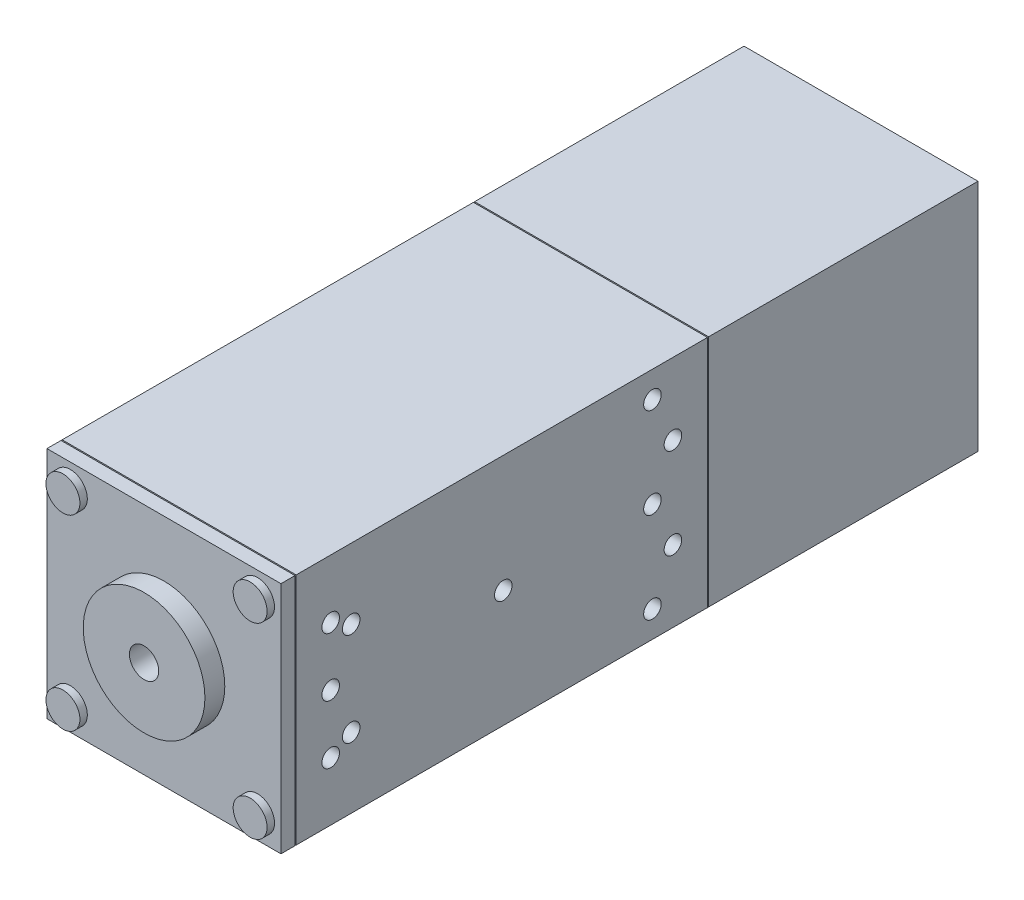
SolidWorks part; units mm, degrees
ref_plane "Alzado" through (0, 0, 0) normal (0, 0, 1) x (1, 0, 0)
ref_plane "Planta" through (0, 0, 0) normal (0, 1, 0) x (1, 0, 0)
ref_plane "Vista lateral" through (0, 0, 0) normal (1, 0, 0) x (0, 0, -1)
sketch "Croquis1" plane through (0, 0, 0) normal (0, 0, 1) x (1, 0, 0)
  line L1 (-20, 20) -> (20, 20)
  line L2 (-20, 20) -> (-20, -20)
  line L3 (-20, -20) -> (20, -20)
  line L4 (20, 20) -> (20, -20)
  line L5 (-20, 20) -> (20, -20) construction
  line L6 (-20, -20) -> (20, 20) construction
  point P0 (0, 0)
  dimension "D2" = 40
extrude "Saliente-Extruir1" add sketch "Croquis1" against normal blind 119.15
sketch "Croquis2" plane through (0, 0, 0) normal (0, 0, 1) x (1, 0, 0)
  circle A0 centre (0, 0) radius 10.4
  dimension "D1" = 20.8
extrude "Saliente-Extruir2" add sketch "Croquis2" along normal blind 3.4
sketch "Croquis3" plane through (0, 0, 0) normal (0, 0, 1) x (1, 0, 0)
  line L0 (20, 20) -> (-20, 20) construction
  line L1 (-16, 16) -> (16, 16)
  line L2 (-16, 16) -> (-16, -16)
  line L3 (-16, -16) -> (16, -16)
  line L4 (16, 16) -> (16, -16)
  line L5 (-16, 16) -> (16, -16) construction
  line L6 (-16, -16) -> (16, 16) construction
  circle A0 centre (16, 16) radius 2.9
  circle A1 centre (-16, 16) radius 2.9
  circle A2 centre (-16, -16) radius 2.9
  circle A3 centre (16, -16) radius 2.9
  point P0 (0, 0)
  dimension "D1" = 5.8
  dimension "D2" = 4
extrude "Saliente-Extruir3" add sketch "Croquis3" along normal blind 1.27 contours L1 A1 L2 | L2 A1 L1 | L1 A0 L4 | L4 A0 L1 | L2 A2 L3 | L3 A2 L2 | L4 A3 L3
sketch "Croquis4" plane through (0, 0, 3.4) normal (0, 0, 1) x (1, 0, 0)
  circle A0 centre (0, 0) radius 2.5
  dimension "D1" = 5
extrude "Cortar-Extruir1" cut sketch "Croquis4" against normal blind 5
sketch "Croquis5" plane through (0, 0, -119.15) normal (0, 0, -1) x (-1, 0, 0)
  line L0 (0, 0) -> (0, -20) construction
  line L1 (20, -20) -> (-20, -20) construction
  line L3 (-4.5, -14) -> (4.5, -14)
  line L4 (-4.5, -14) -> (-4.5, -20)
  line L5 (-4.5, -20) -> (4.5, -20)
  line L6 (4.5, -14) -> (4.5, -20)
  line L7 (-4.5, -14) -> (4.5, -20) construction
  line L8 (-4.5, -20) -> (4.5, -14) construction
  point P5 (0, -17)
  dimension "D1" = 6
  dimension "D2" = 9
extrude "Cortar-Extruir2" cut sketch "Croquis5" against normal blind 9
sketch "Croquis6" plane through (20, 0, 0) normal (1, 0, 0) x (0, 0, -1)
  line L0 (0, 0) -> (119.15, 0) construction
  line L1 (119.15, -20) -> (119.15, 20) construction
  line L2 (63.5, 15.5) -> (63.5, -15.5) construction
  line L3 (67, 7.75) -> (67, -7.75) construction
  line L4 (8.5, 10) -> (8.5, -10) construction
  line L5 (12, 8) -> (12, -8) construction
  line L6 (0, -20) -> (0, 20) construction
  circle A0 centre (38, 0) radius 1.5
  circle A1 centre (8.5, 0) radius 1.5
  circle A2 centre (63.5, 0) radius 1.5
  circle A3 centre (12, 8) radius 1.5
  circle A4 centre (12, -8) radius 1.5
  circle A5 centre (8.5, -10) radius 1.5
  circle A6 centre (8.5, 10) radius 1.5
  circle A7 centre (67, -7.75) radius 1.5
  circle A8 centre (63.5, -15.5) radius 1.5
  circle A9 centre (67, 7.75) radius 1.5
  circle A10 centre (63.5, 15.5) radius 1.5
  point P14 (63.5, 0)
  point P17 (67, 0)
  point P20 (8.5, 0)
  point P23 (12, 0)
  dimension "D1" = 3
  dimension "D2" = 8
  dimension "D3" = 10
  dimension "D4" = 8.5
  dimension "D5" = 3.5
  dimension "D6" = 3.5
  dimension "D7" = 26
  dimension "D8" = 25.5
  dimension "D9" = 7.75
  dimension "D10" = 15.5
  dimension "D11" = 7.75
extrude "Cortar-Extruir3" cut sketch "Croquis6" against normal blind 3.5
sketch "Croquis7" plane through (20, 0, 0) normal (1, 0, 0) x (0, 0, -1)
  line L0 (2.5, 20) -> (2.5, -20) construction
  line L1 (119.15, 20) -> (0, 20) construction
  line L2 (119.15, -20) -> (0, -20) construction
  line L3 (73, 20) -> (73, -20) construction
  circle A0 centre (8.5, 0) radius 1.5 construction
  circle A1 centre (67, 7.75) radius 1.5 construction
  dimension "D1" = 6
  dimension "D2" = 6
sketch "Croquis9" plane through (0, 0, -119.15) normal (0, 0, -1) x (-1, 0, 0)
  line L0 (-6.8298, -20) -> (-6.8298, -11.6505)
  line L1 (-4.5, -20) -> (-20, -20) construction
  line L2 (-6.8298, -11.6505) -> (6.8298, -11.6505)
  line L3 (6.8298, -11.6505) -> (6.8298, -20)
  line L4 (20, -20) -> (4.5, -20) construction
  line L5 (6.8298, -20) -> (4.5, -20)
  line L6 (4.5, -20) -> (4.5, -14)
  line L7 (4.5, -14) -> (-4.5, -14)
  line L8 (-4.5, -14) -> (-4.5, -20)
  line L9 (-4.5, -20) -> (-6.8298, -20)
extrude "Saliente-Extruir4" add sketch "Croquis9" along normal blind 8
sketch "Croquis10" plane through (20, 0, 0) normal (1, 0, 0) x (0, 0, -1)
  line L0 (73, 20) -> (73, -20) construction
  line L1 (73.1, 20) -> (72.9, 20)
  line L2 (73.1, 20) -> (73.1, -20)
  line L3 (73.1, -20) -> (72.9, -20)
  line L4 (72.9, 20) -> (72.9, -20)
  line L5 (73.1, 20) -> (72.9, -20) construction
  line L6 (73.1, -20) -> (72.9, 20) construction
  line L7 (119.15, -20) -> (0, -20) construction
  line L8 (2.5, 20) -> (2.5, -20) construction
  line L9 (2.6, 20) -> (2.4, 20)
  line L10 (2.6, 20) -> (2.6, -20)
  line L11 (2.6, -20) -> (2.4, -20)
  line L12 (2.4, 20) -> (2.4, -20)
  line L13 (2.6, 20) -> (2.4, -20) construction
  line L14 (2.6, -20) -> (2.4, 20) construction
  point P0 (73, 0)
  point P9 (2.5, 0)
  dimension "D1" = 0.2
  dimension "D2" = 0.2
extrude "Cortar-Extruir4" cut sketch "Croquis10" against normal blind 0.2
sketch "Croquis12" plane through (20, 0, 0) normal (1, 0, 0) x (0, 0, -1)
  line L0 (73.1, 0) -> (119.15, 0) construction
  line L1 (73.1, -20) -> (73.1, 20) construction
  line L2 (119.15, -20) -> (119.15, 20) construction
  line L3 (119.15, 20) -> (73.1, 20) construction
  line L4 (76.6, 15) -> (86.6, 15)
  line L5 (76.6, 15) -> (76.6, -15)
  line L6 (76.6, -15) -> (86.6, -15)
  line L7 (86.6, 15) -> (86.6, -15)
  line L8 (76.6, 15) -> (86.6, -15) construction
  line L9 (76.6, -15) -> (86.6, 15) construction
  line L10 (90.1, 15) -> (102.15, 15)
  line L11 (90.1, 15) -> (90.1, -15)
  line L12 (90.1, -15) -> (102.15, -15)
  line L13 (102.15, 15) -> (102.15, -15)
  line L14 (90.1, 15) -> (102.15, -15) construction
  line L15 (90.1, -15) -> (102.15, 15) construction
  line L16 (117.15, 15) -> (103.95, 15)
  line L17 (117.15, 15) -> (117.15, -15)
  line L18 (117.15, -15) -> (103.95, -15)
  line L19 (103.95, 15) -> (103.95, -15)
  line L20 (117.15, 15) -> (103.95, -15) construction
  line L21 (117.15, -15) -> (103.95, 15) construction
  line L23 (119.15, -20) -> (73.1, -20) construction
  line L24 (76.6, 20) -> (117.15, 20)
  line L25 (76.6, 20) -> (76.6, 19.5)
  line L26 (76.6, 19.5) -> (117.15, 19.5)
  line L27 (117.15, 20) -> (117.15, 19.5)
  line L28 (117.15, -20) -> (76.6, -20)
  line L29 (117.15, -20) -> (117.15, -19.5)
  line L30 (117.15, -19.5) -> (76.6, -19.5)
  line L31 (76.6, -20) -> (76.6, -19.5)
  point P6 (81.6, 0)
  point P11 (96.125, 0)
  point P16 (110.55, 0)
  dimension "D1" = 5
  dimension "D2" = 3.5
  dimension "D3" = 2
  dimension "D4" = 3.5
  dimension "D5" = 1.8
  dimension "D6" = 10
  dimension "D7" = 0.5
extrude "Cortar-Extruir5" [suppressed] cut sketch "Croquis12" against normal blind 4
pattern_circular "MatrizC1" count 4 over 360 about axis through (0, 0, 0) along (0, 0, 1) of "Cortar-Extruir4", "Cortar-Extruir5"
fillet "Redondeo1" [suppressed] radius 2
sketch "Croquis13" plane through (0, 20, 0) normal (0, 1, 0) x (1, 0, 0)
  line L1 (-11.9743, 60.1724) -> (11.9743, 60.1724)
  line L2 (-11.9743, 60.1724) -> (-11.9743, 9.6995)
  line L3 (-11.9743, 9.6995) -> (11.9743, 9.6995)
  line L4 (11.9743, 60.1724) -> (11.9743, 9.6995)
  line L5 (-11.9743, 60.1724) -> (11.9743, 9.6995) construction
  line L6 (-11.9743, 9.6995) -> (11.9743, 60.1724) construction
  line L7 (-8.5458, 60.1724) -> (-6.1243, 60.1724)
  line L8 (-8.5458, 60.1724) -> (-8.5458, 9.6995)
  line L9 (-8.5458, 9.6995) -> (-6.1243, 9.6995)
  line L10 (-6.1243, 60.1724) -> (-6.1243, 9.6995)
  line L11 (-2.0157, 60.1724) -> (1.0943, 60.1724)
  line L12 (-2.0157, 60.1724) -> (-2.0157, 9.6995)
  line L13 (-2.0157, 9.6995) -> (1.0943, 9.6995)
  line L14 (1.0943, 60.1724) -> (1.0943, 9.6995)
  line L15 (5.8338, 60.1724) -> (8.7945, 60.1724)
  line L16 (5.8338, 60.1724) -> (5.8338, 9.6995)
  line L17 (5.8338, 9.6995) -> (8.7945, 9.6995)
  line L18 (8.7945, 60.1724) -> (8.7945, 9.6995)
  point P0 (0, 34.9359)
extrude "Cortar-Extruir6" [suppressed] cut sketch "Croquis13" against normal blind 2 contours L8 L1 L2 L3 | L12 L1 L10 L3 | L16 L1 L14 L3 | L1 L18 L3 L4
pattern_circular "MatrizC2" [suppressed] count 4 over 360
sketch "Croquis14" plane through (0, 0, 3.4) normal (0, 0, 1) x (1, 0, 0)
  point P0 (0, 0)
sketch "Croquis15" plane through (0, 0, 0) normal (0, 1, 0) x (1, 0, 0)
  line L0 (0, -3.4) -> (0, -16) construction
  dimension "D1" = 12.6
